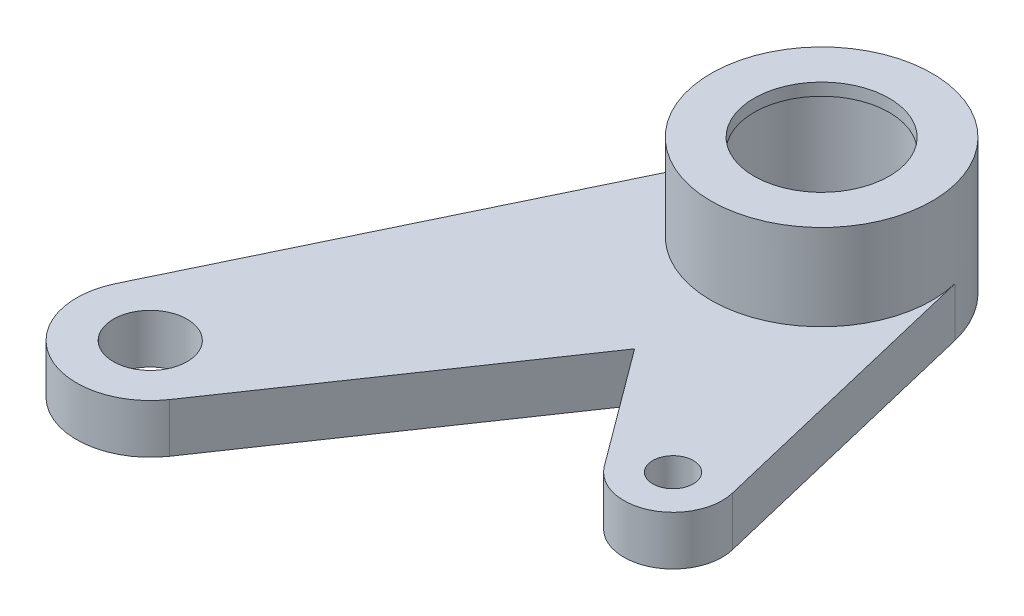
SolidWorks part; units mm, degrees
ref_plane "前视基准面" through (0, 0, 0) normal (0, 0, 1) x (1, 0, 0)
ref_plane "上视基准面" through (0, 0, 0) normal (0, 1, 0) x (1, 0, 0)
ref_plane "右视基准面" through (0, 0, 0) normal (1, 0, 0) x (0, 0, -1)
sketch "草图1" plane through (0, 0, 0) normal (0, 1, 0) x (1, 0, 0)
  line L0 (0, 0) -> (-20, -34.641) construction
  line L1 (0, 0) -> (10.5655, -22.6577) construction
  line L2 (0, 0) -> (0, -52.8876) construction
  line L3 (-8.1098, 3.9028) -> (-25.4065, -32.0392)
  line L4 (0.303, -15.5263) -> (-15.0435, -38.0223)
  line L5 (8.7527, 2.0954) -> (14.4555, -21.7264)
  line L7 (7.3516, -25.0391) -> (0.303, -15.5263)
  arc A0 (7.3516, -25.0391) -> (14.4555, -21.7264) centre (10.5655, -22.6577) ccw
  arc A1 (8.7527, 2.0954) -> (-8.1098, 3.9028) centre (0, 0) ccw
  arc A2 (-25.4065, -32.0392) -> (-15.0435, -38.0223) centre (-20, -34.641) ccw
  dimension "D1" = 25
  dimension "D2" = 18
  dimension "D6" = 12
  dimension "D8" = 8
  dimension "D3" = 25
  dimension "D4" = 40
  dimension "D5" = 30
extrude "凸台-拉伸1" add sketch "草图1" along normal blind 4
sketch "草图3" plane through (0, 4, 0) normal (0, 1, 0) x (1, 0, 0)
  circle A0 centre (0, 0) radius 9
extrude "凸台-拉伸2" add sketch "草图3" along normal blind 7
sketch "草图4" plane through (0, 4, 0) normal (0, 1, 0) x (1, 0, 0)
  circle A0 centre (-20, -34.641) radius 3
  dimension "D1" = 6
extrude "切除-拉伸1" cut sketch "草图4" against normal through all
sketch "草图5" plane through (0, 0, 0) normal (0, -1, 0) x (1, 0, 0)
  circle A0 centre (0, 0) radius 6
  dimension "D1" = 12
extrude "切除-拉伸2" cut sketch "草图5" against normal blind 10
sketch "草图7" plane through (0, 11, 0) normal (0, 1, 0) x (1, 0, 0)
  circle A0 centre (0, 0) radius 5.5
  dimension "D1" = 11
extrude "切除-拉伸3" cut sketch "草图7" against normal through all
hole_wizard "M4 螺纹孔1" positions "草图9" profile "草图8" tap size "M4" standard "GB" end condition through all
sketch "草图9" plane through (0, 4, 0) normal (0, 1, 0) x (1, 0, 0)
  point P0 (10.5655, -22.6577)
sketch "草图8" plane through (10.5655, 4, 22.6577) normal (1, 0, 0) x (0, 0, 1)
  line L0 (0, 0) -> (0, 4)
  line L1 (0, 4) -> (1.65, 4)
  line L2 (1.65, 4) -> (1.65, 0)
  line L5 (1.65, 0) -> (0, 0)
  line L11 (0, -6.35) -> (0, 107.95) construction
  dimension "通孔螺纹孔钻头直径" = 3.3
  dimension "通孔螺纹孔钻头深度" = 4
cosmetic thread "孔螺蚊线1" parameters "D2"=4
scale "Scale1" scale about centroid uniform scaling yes scale factor 2
